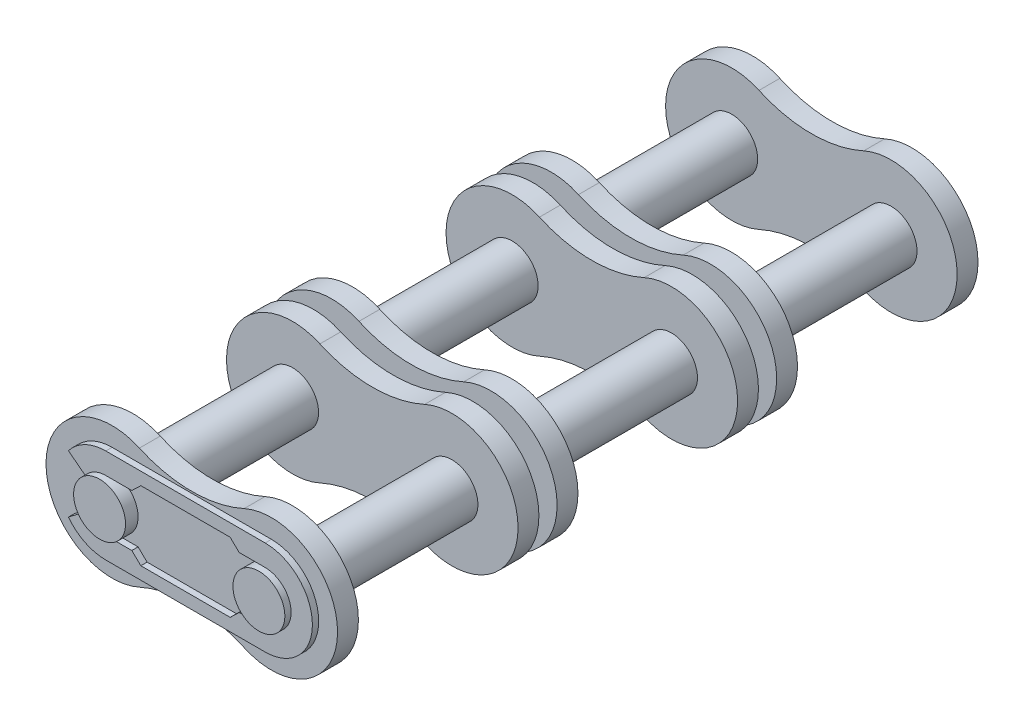
SolidWorks part; units mm, degrees
material "Stahl schwarz"
ref_plane "Vorne" through (0, 0, 0) normal (0, 0, 1) x (1, 0, 0)
ref_plane "Oben" through (0, 0, 0) normal (0, 1, 0) x (1, 0, 0)
ref_plane "Rechts" through (0, 0, 0) normal (1, 0, 0) x (0, 0, -1)
sketch "Skizze1" plane through (0, 0, 0) normal (0, 0, 1) x (1, 0, 0)
  line L0 (32.0993, 0) -> (-33.7315, 0) construction
  line L1 (0, 36.0248) -> (0, -15.2525) construction
  arc A0 (-8.351, 9.6009) -> (-8.351, -9.6009) centre (-12.7, 0) ccw
  arc A1 (8.351, -9.6009) -> (8.351, 9.6009) centre (12.7, 0) ccw
  arc A2 (-8.351, 9.6009) -> (8.351, 9.6009) centre (0, 28.0364) ccw
  arc A3 (-8.351, -9.6009) -> (8.351, -9.6009) centre (0, -28.0364) cw
  dimension "D1" = 21.08
  dimension "D2" = 28.0364
  dimension "D3" = 25.4
extrude "Aufsatz-Linear austragen1" add sketch "Skizze1" along normal mid plane 36.1
sketch "Skizze3" plane through (0, 0, 0) normal (0, 0, 1) x (1, 0, 0)
  line L0 (0, 4.869) -> (0, -5.0928) construction
  line L1 (24.4568, 0) -> (-24.6247, 0) construction
  circle A0 centre (-12.7, 0) radius 4.14
  circle A1 centre (12.7, 0) radius 4.14
  arc A2 (-8.351, 9.6009) -> (-8.351, -9.6009) centre (-12.7, 0) ccw
  arc A3 (8.351, -9.6009) -> (8.351, 9.6009) centre (12.7, 0) ccw
  arc A4 (-8.351, 9.6009) -> (8.351, 9.6009) centre (0, 28.0364) ccw
  arc A5 (-8.351, -9.6009) -> (8.351, -9.6009) centre (0, -28.0364) cw
  dimension "D1" = 8.28
  dimension "D3" = 21.08
  dimension "D2" = 25.4
  dimension "D4" = 28.0364
extrude "Schnitt-Linear austragen1" cut sketch "Skizze3" against normal mid plane 25.45
sketch "Skizze4" plane through (0, 0, 18.05) normal (0, 0, 1) x (1, 0, 0)
  line L0 (0, 10.2137) -> (0, -10.0737) construction
  line L1 (23.9531, 0) -> (-23.8972, 0) construction
  arc A0 (-8.351, 9.6009) -> (-8.351, -9.6009) centre (-12.7, 0) ccw
  arc A1 (8.351, -9.6009) -> (8.351, 9.6009) centre (12.7, 0) ccw
  arc A2 (-8.351, 9.6009) -> (8.351, 9.6009) centre (0, 28.0364) ccw
  arc A3 (-8.351, -9.6009) -> (8.351, -9.6009) centre (0, -28.0364) cw
  circle A4 centre (-12.7, 0) radius 4.14
  circle A5 centre (12.7, 0) radius 4.14
  dimension "D1" = 21.08
  dimension "D2" = 25.4
  dimension "D4" = 8.28
  dimension "D3" = 28.0364
extrude "Schnitt-Linear austragen2" cut sketch "Skizze4" against normal blind 2
mirror "Spiegeln1" about plane through (0, 0, 0) normal (0, 0, 1) of "Schnitt-Linear austragen2"
sketch "Skizze5" plane through (0, 0, 16.05) normal (0, 0, 1) x (1, 0, 0)
  line L0 (-24.0651, 0) -> (23.7852, 0) construction
  line L1 (-18.6728, 4.5831) -> (-15.9845, 2.5203)
  line L2 (12.7, 7.5286) -> (-12.7, 7.5286)
  line L3 (12.7, 4.14) -> (8.56, 4.14)
  line L4 (8.56, 4.14) -> (7.1206, 5.5286)
  line L5 (-7.1206, 5.5286) -> (7.1206, 5.5286)
  line L6 (-12.7, 4.14) -> (-8.56, 4.14)
  line L7 (-8.56, 4.14) -> (-7.1206, 5.5286)
  line L8 (-8.56, -4.14) -> (-7.1206, -5.5286)
  line L9 (-12.7, -4.14) -> (-8.56, -4.14)
  line L10 (-7.1206, -5.5286) -> (7.1206, -5.5286)
  line L11 (8.56, -4.14) -> (7.1206, -5.5286)
  line L12 (12.7, -4.14) -> (8.56, -4.14)
  line L13 (12.7, -7.5286) -> (-12.7, -7.5286)
  line L14 (-18.6728, -4.5831) -> (-15.9845, -2.5203)
  arc A0 (-12.7, 4.14) -> (-15.9845, 2.5203) centre (-12.7, 0) ccw
  arc A1 (12.7, -4.14) -> (12.7, 4.14) centre (12.7, 0) ccw
  arc A2 (12.7, -7.5286) -> (12.7, 7.5286) centre (12.7, 0) ccw
  arc A3 (-12.7, 7.5286) -> (-18.6728, 4.5831) centre (-12.7, 0) ccw
  arc A6 (-12.7, -7.5286) -> (-18.6728, -4.5831) centre (-12.7, 0) cw
  arc A7 (-12.7, -4.14) -> (-15.9845, -2.5203) centre (-12.7, 0) cw
  dimension "D1" = 15.0571
  dimension "D2" = 8.28
  dimension "D3" = 2
  dimension "D4" = 2
  dimension "D5" = 4.14
  dimension "D6" = 75
extrude "Aufsatz-Linear austragen2" add sketch "Skizze5" along normal blind 1
pattern_linear "Lineares Muster1" [suppressed] count 2 spacing 35
pattern_linear "Lineares Muster3" [suppressed] count 2 spacing 18.5
pattern_linear "Lineares Muster4" [suppressed] count 2 spacing 20.86
pattern_linear "Lineares Muster5" [suppressed] count 2 spacing 17
pattern_linear "Lineares Muster6" count 3 spacing 35 along (0, 0, -1) of "Aufsatz-Linear austragen1", "Schnitt-Linear austragen1", "Schnitt-Linear austragen2", "Spiegeln1"
pattern_linear "Lineares Muster7" [suppressed] count 2 spacing 22.5
pattern_linear "Lineares Muster8" [suppressed] count 3 spacing 20.86
equation "\"Teilung p\"= \"D3@Skizze1\""
equation "\"Durchmesser g\"= \"D1@Skizze1\""
equation "\"Hilfsmaß\"= \"D2@Skizze1\""
equation "\"Bolzendurchmesser\"= \"D1@Skizze3\""
equation "\"D2@Skizze3\"=\"Teilung p\""
equation "\"D3@Skizze3\"=\"Durchmesser g\""
equation "\"D4@Skizze3\"=\"Hilfsmaß\""
equation "\"D1@Skizze4\"=\"Durchmesser g\""
equation "\"D2@Skizze4\"=\"Teilung p\""
equation "\"D3@Skizze4\"=\"Hilfsmaß\""
equation "\"D4@Skizze4\"=\"Bolzendurchmesser\""
equation "\"D2@Skizze5\"=\"Bolzendurchmesser\""
equation "\"D2@Skizze1\"=\"Durchmesser g\" * 1.33"
equation "\"D5@Skizze5\"=\"Bolzendurchmesser\" / 2"
equation "\"D1@Skizze5\"=\"Durchmesser g\" / 1.4"
